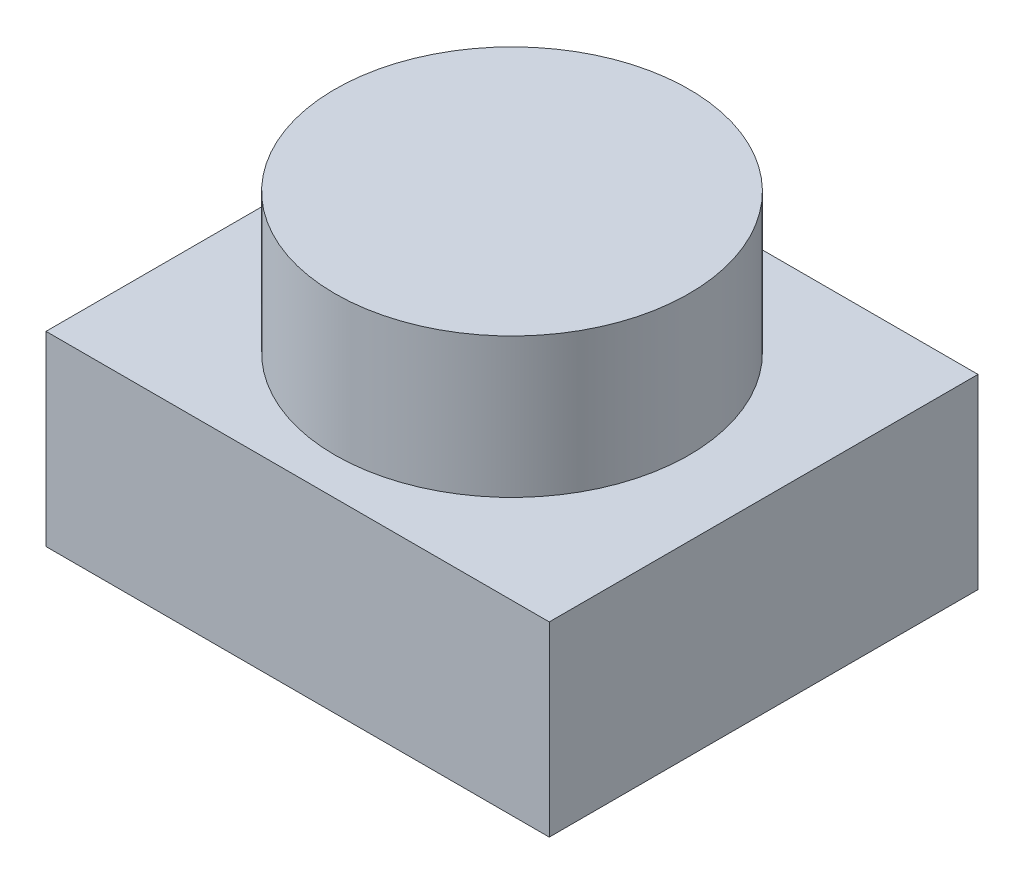
SolidWorks part; units mm, degrees
ref_plane "Front Plane" through (0, 0, 0) normal (0, 0, 1) x (1, 0, 0)
ref_plane "Top Plane" through (0, 0, 0) normal (0, 1, 0) x (1, 0, 0)
ref_plane "Right Plane" through (0, 0, 0) normal (1, 0, 0) x (0, 0, -1)
sketch "SK_P01_Base" plane through (0, 0, 0) normal (0, 1, 0) x (1, 0, 0)
  line L0 (-27, -23) -> (27, -23)
  line L1 (27, -23) -> (27, 23)
  line L2 (27, 23) -> (-27, 23)
  line L3 (-27, 23) -> (-27, -23)
extrude "P01_Base" add sketch "SK_P01_Base" along normal blind 20
sketch "SK_P02_Head" plane through (0, 0, 0) normal (0, 1, 0) x (1, 0, 0)
  circle A0 centre (0, 0) radius 19
extrude "P02_Head" add sketch "SK_P02_Head" along normal blind 15 from offset 20
